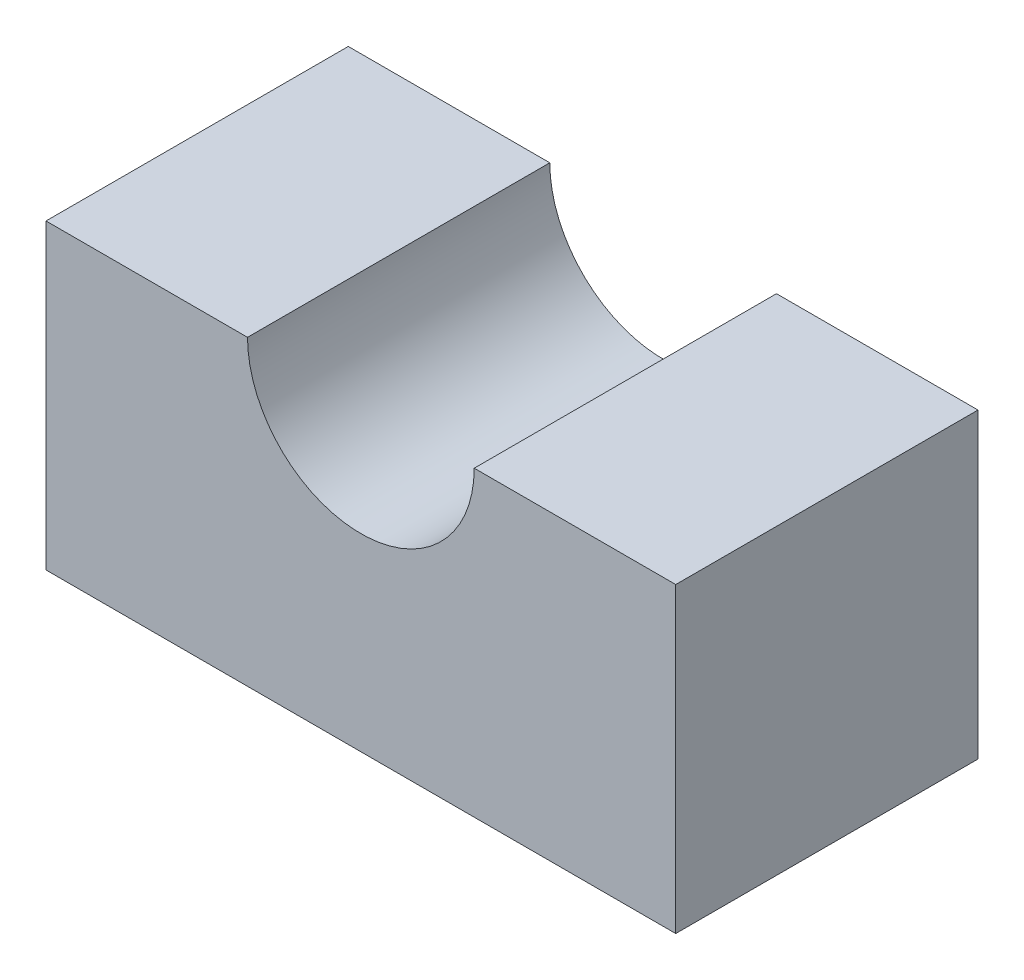
SolidWorks part; units mm, degrees
ref_plane "Front Plane" through (0, 0, 0) normal (0, 0, 1) x (1, 0, 0)
ref_plane "Top Plane" through (0, 0, 0) normal (0, 1, 0) x (1, 0, 0)
ref_plane "Right Plane" through (0, 0, 0) normal (1, 0, 0) x (0, 0, -1)
sketch "Sketch1" plane through (0, 0, 0) normal (0, 0, 1) x (1, 0, 0)
  line L0 (-12.5, 0) -> (12.5, 0)
  line L1 (12.5, 0) -> (12.5, 12)
  line L2 (12.5, 12) -> (4.5, 12)
  line L3 (-12.5, 12) -> (-12.5, 0)
  line L4 (-4.5, 12) -> (-12.5, 12)
  line L5 (-4.5, 12) -> (4.5, 12) construction
  arc A0 (-4.5, 12) -> (4.5, 12) centre (0, 12) ccw
  dimension "D3" = 9
  dimension "D1" = 12
  dimension "D2" = 25
extrude "Boss-Extrude1" add sketch "Sketch1" along normal mid plane 12
